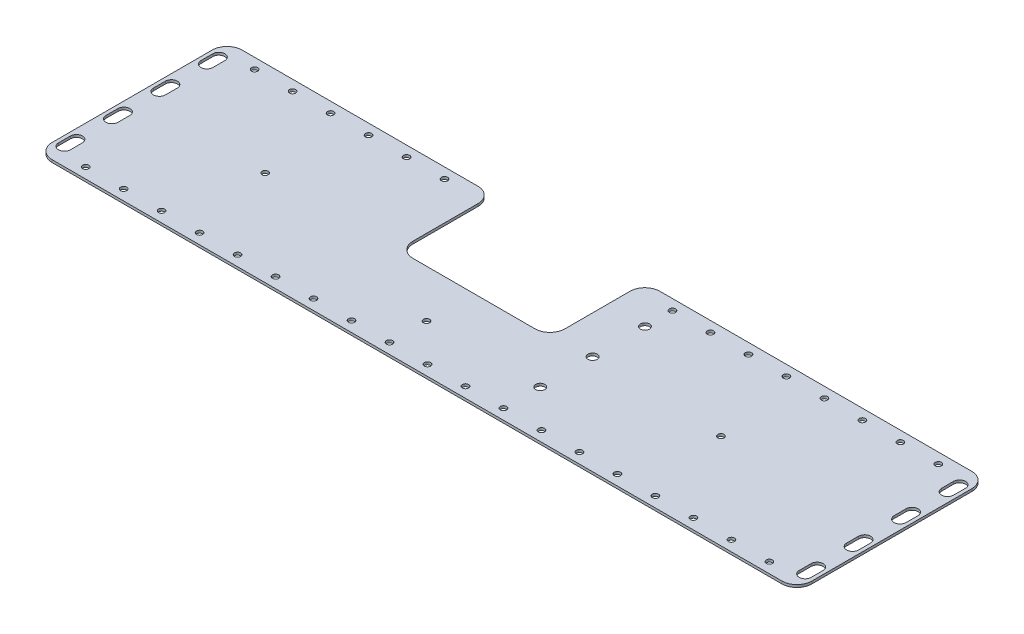
SolidWorks part; units mm, degrees
material "6061-T6 (SS)"
ref_plane "Front Plane" through (0, 0, 0) normal (0, 0, 1) x (1, 0, 0)
ref_plane "Top Plane" through (0, 0, 0) normal (0, 1, 0) x (1, 0, 0)
ref_plane "Right Plane" through (0, 0, 0) normal (1, 0, 0) x (0, 0, -1)
sketch "Sketch1" plane through (0, 0, 0) normal (0, 1, 0) x (1, 0, 0)
  line L1 (-254, 63.5) -> (254, 63.5)
  line L2 (-254, 63.5) -> (-254, -63.5)
  line L3 (-254, -63.5) -> (254, -63.5)
  line L4 (254, 63.5) -> (254, -63.5)
  line L5 (-254, 63.5) -> (254, -63.5) construction
  line L6 (-254, -63.5) -> (254, 63.5) construction
  point P0 (0, 0)
  dimension "D1" = 127
  dimension "D2" = 508
extrude "Boss-Extrude1" add sketch "Sketch1" along normal mid plane 1.7 contours L1 L4 L3 L2
sketch "Sketch2" plane through (0, 0.85, 0) normal (0, 1, 0) x (1, 0, 0)
  line L0 (247.65, 63.5) -> (247.65, -63.5) construction
  line L1 (-254, 63.5) -> (254, 63.5) construction
  line L2 (-254, -63.5) -> (254, -63.5) construction
  line L3 (247.65, 0) -> (0, 0) construction
  line L4 (0, 0) -> (0, -63.5) construction
  line L5 (123.825, 0) -> (123.825, -63.5) construction
  line L6 (123.825, -31.75) -> (247.65, -31.75) construction
  line L7 (185.7375, -31.75) -> (185.7375, -63.5) construction
  line L8 (247.65, -43.625) -> (247.65, -51.625) construction
  line L9 (251.65, -43.625) -> (251.65, -51.625)
  line L10 (243.65, -43.625) -> (243.65, -51.625)
  line L11 (247.65, -19.875) -> (247.65, -11.875) construction
  line L14 (251.65, -19.875) -> (251.65, -11.875)
  line L17 (243.65, -19.875) -> (243.65, -11.875)
  line L20 (247.65, 19.875) -> (247.65, 11.875) construction
  line L21 (251.65, 19.875) -> (251.65, 11.875)
  line L22 (243.65, 19.875) -> (243.65, 11.875)
  line L23 (247.65, 43.625) -> (247.65, 51.625) construction
  line L24 (251.65, 43.625) -> (251.65, 51.625)
  line L25 (243.65, 43.625) -> (243.65, 51.625)
  line L26 (-247.65, 43.625) -> (-247.65, 51.625) construction
  line L27 (-251.65, 43.625) -> (-251.65, 51.625)
  line L28 (-243.65, 43.625) -> (-243.65, 51.625)
  line L29 (-247.65, 19.875) -> (-247.65, 11.875) construction
  line L30 (-251.65, 19.875) -> (-251.65, 11.875)
  line L31 (-243.65, 19.875) -> (-243.65, 11.875)
  line L32 (-247.65, -19.875) -> (-247.65, -11.875) construction
  line L33 (-251.65, -19.875) -> (-251.65, -11.875)
  line L34 (-243.65, -19.875) -> (-243.65, -11.875)
  line L35 (-247.65, -43.625) -> (-247.65, -51.625) construction
  line L36 (-251.65, -43.625) -> (-251.65, -51.625)
  line L37 (-243.65, -43.625) -> (-243.65, -51.625)
  arc A0 (251.65, -43.625) -> (243.65, -43.625) centre (247.65, -43.625) ccw
  arc A1 (243.65, -51.625) -> (251.65, -51.625) centre (247.65, -51.625) ccw
  arc A8 (251.65, -19.875) -> (243.65, -19.875) centre (247.65, -19.875) cw
  arc A9 (243.65, -11.875) -> (251.65, -11.875) centre (247.65, -11.875) cw
  arc A10 (251.65, 19.875) -> (243.65, 19.875) centre (247.65, 19.875) ccw
  arc A11 (243.65, 11.875) -> (251.65, 11.875) centre (247.65, 11.875) ccw
  arc A12 (251.65, 43.625) -> (243.65, 43.625) centre (247.65, 43.625) cw
  arc A13 (243.65, 51.625) -> (251.65, 51.625) centre (247.65, 51.625) cw
  arc A14 (-251.65, 43.625) -> (-243.65, 43.625) centre (-247.65, 43.625) ccw
  arc A15 (-243.65, 51.625) -> (-251.65, 51.625) centre (-247.65, 51.625) ccw
  arc A16 (-251.65, 19.875) -> (-243.65, 19.875) centre (-247.65, 19.875) cw
  arc A17 (-243.65, 11.875) -> (-251.65, 11.875) centre (-247.65, 11.875) cw
  arc A18 (-251.65, -19.875) -> (-243.65, -19.875) centre (-247.65, -19.875) ccw
  arc A19 (-243.65, -11.875) -> (-251.65, -11.875) centre (-247.65, -11.875) ccw
  arc A20 (-251.65, -43.625) -> (-243.65, -43.625) centre (-247.65, -43.625) cw
  arc A21 (-243.65, -51.625) -> (-251.65, -51.625) centre (-247.65, -51.625) cw
  point P18 (247.65, -47.625)
  point P24 (185.7375, -47.625)
  point P27 (247.65, -15.875)
  point P34 (247.65, 15.875)
  point P41 (247.65, 47.625)
  point P48 (-247.65, 47.625)
  point P55 (-247.65, 15.875)
  point P62 (-247.65, -15.875)
  point P69 (-247.65, -47.625)
  dimension "D3" = 4
  dimension "D1" = 247.65
  dimension "D2" = 8
extrude "Cut-Extrude1" cut sketch "Sketch2" against normal through all both and the other way through all
fillet "Fillet1" radius 10 4 edges at (-254, 0, -63.5) (254, 0, 63.5) (-254, 0, 63.5) (254, 0, -63.5)
sketch "Sketch3" plane through (0, 0.85, 0) normal (0, 1, 0) x (1, 0, 0)
  line L0 (-244, 63.5) -> (244, 63.5) construction
  line L1 (-76.2, 63.5) -> (25.4, 63.5)
  line L2 (-76.2, 63.5) -> (-76.2, 0)
  line L3 (-76.2, 0) -> (25.4, 0)
  line L4 (25.4, 63.5) -> (25.4, 0)
  line L7 (254, 53.5) -> (254, -53.5) construction
  dimension "D1" = 63.5
  dimension "D2" = 101.6
  dimension "D3" = 228.6
extrude "Cut-Extrude2" cut sketch "Sketch3" against normal through all
fillet "Fillet2" radius 10 4 edges at (25.4, 0, 0) (25.4, 0, -63.5) (-76.2, 0, 0) (-76.2, 0, -63.5)
sketch "Sketch8" plane through (0, 0.85, 0) normal (0, 1, 0) x (1, 0, 0)
  line L0 (-165.1, 63.5) -> (-165.1, -63.5) construction
  line L1 (-244, 63.5) -> (-86.2, 63.5) construction
  line L2 (-244, -63.5) -> (244, -63.5) construction
  line L3 (139.7, 63.5) -> (139.7, -63.5) construction
  line L4 (35.4, 63.5) -> (244, 63.5) construction
  line L5 (-25.4, 0) -> (-25.4, -63.5) construction
  line L6 (-66.2, 0) -> (15.4, 0) construction
  line L7 (0, 0) -> (0, -63.5) construction
  line L8 (254, -56.5) -> (-254, -56.5) construction
  line L9 (-254, 53.5) -> (-254, -53.5) construction
  line L10 (-254, 56.5) -> (-228.6, 56.5) construction
  line L11 (-228.6, 56.5) -> (-228.6, 63.5) construction
  circle A0 centre (-165.1, 0) radius 2.07
  circle A1 centre (-25.4, -31.75) radius 2.07
  circle A2 centre (139.7, 0) radius 2.07
  circle A3 centre (-228.6, -56.5) radius 2.07
  circle A4 centre (-203.2, -56.5) radius 2.07
  circle A5 centre (-177.8, -56.5) radius 2.07
  circle A6 centre (-152.4, -56.5) radius 2.07
  circle A7 centre (-127, -56.5) radius 2.07
  circle A8 centre (-101.6, -56.5) radius 2.07
  circle A9 centre (-76.2, -56.5) radius 2.07
  circle A10 centre (-50.8, -56.5) radius 2.07
  circle A11 centre (-25.4, -56.5) radius 2.07
  circle A12 centre (0, -56.5) radius 2.07
  circle A13 centre (25.4, -56.5) radius 2.07
  circle A14 centre (50.8, -56.5) radius 2.07
  circle A15 centre (76.2, -56.5) radius 2.07
  circle A16 centre (101.6, -56.5) radius 2.07
  circle A17 centre (127, -56.5) radius 2.07
  circle A18 centre (152.4, -56.5) radius 2.07
  circle A19 centre (177.8, -56.5) radius 2.07
  circle A20 centre (203.2, -56.5) radius 2.07
  circle A21 centre (228.6, -56.5) radius 2.07
  circle A22 centre (-228.6, 56.5) radius 2.07
  circle A23 centre (-203.2, 56.5) radius 2.07
  circle A24 centre (-177.8, 56.5) radius 2.07
  circle A25 centre (-152.4, 56.5) radius 2.07
  circle A26 centre (-127, 56.5) radius 2.07
  circle A27 centre (-101.6, 56.5) radius 2.07
  circle A28 centre (-76.2, 56.5) radius 2.07 [skipped]
  circle A29 centre (-50.8, 56.5) radius 2.07 [skipped]
  circle A30 centre (-25.4, 56.5) radius 2.07 [skipped]
  circle A31 centre (0, 56.5) radius 2.07 [skipped]
  circle A32 centre (25.4, 56.5) radius 2.07 [skipped]
  circle A33 centre (50.8, 56.5) radius 2.07
  circle A34 centre (76.2, 56.5) radius 2.07
  circle A35 centre (101.6, 56.5) radius 2.07
  circle A36 centre (127, 56.5) radius 2.07
  circle A37 centre (152.4, 56.5) radius 2.07
  circle A38 centre (177.8, 56.5) radius 2.07
  circle A39 centre (203.2, 56.5) radius 2.07
  circle A40 centre (228.6, 56.5) radius 2.07
  point P26 (0, -56.5)
  dimension "D1" = 4.14
  dimension "D2" = 7
  dimension "D3" = 25.4
  dimension "D5" = 25.4
  dimension "D6" = 7
  dimension "D7" = 25.4
  dimension "D9" = 25.4
  dimension "D4" = 19
  dimension "D8" = 19
extrude "Cut-Extrude3" cut sketch "Sketch8" against normal up to next (1.7 mm away)
sketch "Sketch9" plane through (254, 0, 0) normal (1, 0, 0) x (0, 0, -1)
  line L0 (63.5, 0.85) -> (53.5, 0.85) construction
  line L2 (18.62, 7.2) -> (20.32, 7.2)
  line L3 (18.62, 7.2) -> (18.62, 0.85)
  line L4 (18.62, 0.85) -> (20.32, 0.85)
  line L5 (20.32, 7.2) -> (20.32, 0.85)
  line L6 (63.5, 0.85) -> (63.5, -0.85) construction
  line L7 (53.5, 0.85) -> (-53.5, 0.85) construction
  line L8 (-45.72, 7.2) -> (-44.02, 7.2)
  line L9 (-45.72, 7.2) -> (-45.72, 0.85)
  line L10 (-45.72, 0.85) -> (-44.02, 0.85)
  line L11 (-44.02, 7.2) -> (-44.02, 0.85)
  line L12 (-63.5, -0.85) -> (-63.5, 0.85) construction
  dimension "D1" = 1.7
  dimension "D2" = 43.18
  dimension "D3" = 6.35
  dimension "D4" = 17.78
sketch "Sketch12" plane through (0, 0.85, 0) normal (0, 1, 0) x (1, 0, 0)
  line L0 (25.4, 10) -> (25.4, 53.5) construction
  line L1 (35.4, 63.5) -> (244, 63.5) construction
  circle A0 centre (50.8, 38.1) radius 3.05
  circle A1 centre (50.8, 3.1) radius 3.05
  circle A2 centre (50.8, -31.9) radius 3.05
  dimension "D3" = 6.1
  dimension "D1" = 25.4
  dimension "D2" = 25.4
  dimension "D5" = 35
  dimension "D4" = 3
extrude "Cut-Extrude4" cut sketch "Sketch12" against normal through all
sketch "Sketch13" plane through (0, -78.574, 0) normal (0, 1, 0) x (1, 0, 0)
  circle A0 centre (50.8, -31.9) radius 3.05 construction
  circle A1 centre (50.8, -31.9) radius 3.05
  circle A2 centre (50.8, 3.1) radius 3.05
  circle A3 centre (50.8, 38.1) radius 3.05
  dimension "D2" = 35
  dimension "D1" = 3
